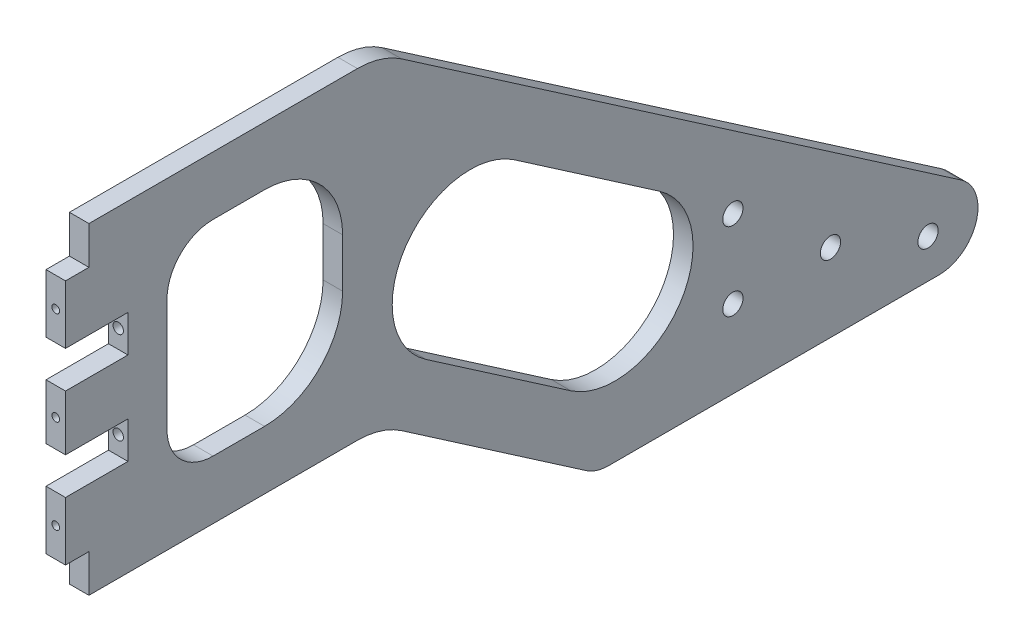
SolidWorks part; units mm, degrees
material "6061 Alloy"
ref_plane "Front Plane" through (0, 0, 0) normal (0, 0, 1) x (1, 0, 0)
ref_plane "Top Plane" through (0, 0, 0) normal (0, 1, 0) x (1, 0, 0)
ref_plane "Right Plane" through (0, 0, 0) normal (1, 0, 0) x (0, 0, -1)
sketch "Sketch1" plane through (0, 0, 0) normal (1, 0, 0) x (0, 0, -1)
  line L0 (124.0703, 0) -> (-28.3297, 0)
  line L1 (55, 0) -> (-55, 0) construction
  line L2 (-28.3297, 0) -> (-98.1797, 48.0219)
  line L3 (-98.1797, 48.0219) -> (-98.1797, 152.7969)
  line L4 (-28.3297, 104.775) -> (124.0703, 0)
  line L5 (-28.3297, 0) -> (-28.3297, 104.775)
  line L6 (-28.3297, 104.775) -> (-98.1797, 152.7969)
  line L7 (-98.1797, 152.7969) -> (-180.7297, 152.7969)
  line L8 (-180.7297, 152.7969) -> (-180.7297, 48.0219)
  line L9 (-180.7297, 48.0219) -> (-98.1797, 48.0219)
  line L10 (-139.4547, 152.7969) -> (-139.4547, 48.0219)
  line L11 (-139.4547, 133.7469) -> (-110.8797, 133.7469)
  line L12 (-110.8797, 133.7469) -> (-110.8797, 67.0719)
  line L13 (-110.8797, 67.0719) -> (-139.4547, 67.0719)
  line L14 (-139.4547, 67.0719) -> (-168.0297, 67.0719)
  line L15 (-168.0297, 67.0719) -> (-168.0297, 133.7469)
  line L16 (-168.0297, 133.7469) -> (-139.4547, 133.7469)
  line L17 (-63.2547, 24.0109) -> (-63.2547, 128.7859)
  line L18 (-63.2547, 76.3984) -> (-28.3297, 52.3875)
  line L19 (-63.2547, 76.3984) -> (-98.1797, 100.4094)
  line L20 (-22.2452, 48.2044) -> (-69.3392, 80.5815) construction
  line L21 (-36.6351, 27.2737) -> (-83.7291, 59.6509)
  line L22 (-7.8554, 69.1351) -> (-54.9494, 101.5122)
  line L23 (-180.7297, 152.7969) -> (-193.4297, 152.7969)
  line L24 (-193.4297, 79.4094) -> (-193.4297, 48.0219)
  line L25 (-193.4297, 48.0219) -> (-180.7297, 48.0219)
  line L26 (-180.7297, 121.4094) -> (-193.4297, 121.4094)
  line L27 (-180.7297, 100.4094) -> (-180.7297, 91.4094)
  line L28 (-180.7297, 91.4094) -> (-193.4297, 91.4094)
  line L29 (-180.7297, 109.4094) -> (-193.4297, 109.4094)
  line L30 (-193.4297, 121.4094) -> (-193.4297, 152.7969)
  line L31 (-193.4297, 91.4094) -> (-193.4297, 109.4094)
  line L32 (-193.4297, 79.4094) -> (-180.7297, 79.4094)
  line L33 (-180.7297, 109.4094) -> (-180.7297, 100.4094)
  line L34 (-180.7297, 100.4094) -> (-180.7297, 91.4094)
  line L35 (-193.4297, 79.4094) -> (-201.0497, 79.4094)
  line L36 (-201.0497, 79.4094) -> (-201.0497, 60.3594)
  line L37 (-201.0497, 60.3594) -> (-193.4297, 60.3594)
  line L38 (-193.4297, 121.4094) -> (-201.0497, 121.4094)
  line L39 (-201.0497, 121.4094) -> (-201.0497, 140.4594)
  line L40 (-201.0497, 140.4594) -> (-193.4297, 140.4594)
  line L41 (-193.4297, 109.4094) -> (-201.0497, 109.4094)
  line L42 (-201.0497, 109.4094) -> (-201.0497, 91.4094)
  line L43 (-201.0497, 91.4094) -> (-193.4297, 91.4094)
  arc A0 (-36.6351, 27.2737) -> (-7.8554, 69.1351) centre (-22.2452, 48.2044) ccw
  arc A1 (-54.9494, 101.5122) -> (-83.7291, 59.6509) centre (-69.3392, 80.5815) ccw
  point P25 (-45.7922, 64.393)
  dimension "D11" = 9
  dimension "D1" = 152.4
  dimension "D2" = 104.775
  dimension "D3" = 152.4
  dimension "D4" = 57.15
  dimension "D5" = 50.8
  dimension "D6" = 82.55
  dimension "D7" = 12.7
  dimension "D8" = 12.7
  dimension "D9" = 19.05
  dimension "D10" = 19.05
  dimension "D12" = 9
  dimension "D13" = 12
  dimension "D14" = 12
  dimension "D15" = 12.7
  dimension "D16" = 19.05
  dimension "D17" = 19.05
  dimension "D18" = 7.62
extrude "Boss-Extrude1" add sketch "Sketch1" along normal blind 6.35 contours A0 L5 L0 L4 L22 | A1 L22 L5 L6 L17 | A1 L17 L6 L3 L19 | A1 L19 L3 L2 L17 L21 | A0 L21 L17 L2 L5 | L12 L13 L10 L9 L3 L7 L11 | L15 L16 L10 L7 L8 L9 L14 | L30 L26 L8 L23 | L40 L39 L38 L30 | L31 L28 L8 L29 | L42 L43 L31 L41 | L36 L37 L24 L35 | L32 L24 L25 L8
fillet "Fillet1" radius 25.4 4 edges at (3.175, 152.7969, 98.1797) (3.175, 48.0219, 98.1797) (3.175, 133.7469, 110.8797) (3.175, 67.0719, 110.8797)
fillet "Fillet2" radius 12.7 2 edges at (3.175, 0, -124.0703) (3.175, 0, 28.3297)
sketch "Sketch3" plane through (6.35, 0, 0) normal (1, 0, 0) x (0, 0, -1)
  line L0 (-28.3297, 0) -> (47.8703, 0)
  line L1 (-31.5802, 2.2347) -> (-91.6789, 43.5525) construction
  line L2 (3.4925, 0) -> (-3.4925, 0) construction
  line L3 (47.8703, 0) -> (47.8703, 25.4)
  line L4 (47.8703, 0) -> (79.6203, 0)
  line L5 (79.6203, 0) -> (79.6203, 12.7)
  line L6 (16.1203, 0) -> (16.1203, 50.8)
  line L7 (47.8703, 25.4) -> (16.1203, 25.4)
  point P5 (47.8703, 25.4)
  point P10 (79.6203, 12.7)
  point P11 (16.1203, 50.8)
  point P13 (16.1203, 25.4)
  dimension "D1" = 76.2
  dimension "D2" = 25.4
  dimension "D3" = 50.8
  dimension "D4" = 31.75
  dimension "D5" = 31.75
  dimension "D6" = 12.7
hole_wizard "M6 Clearance Hole1" positions "Sketch3" profile "Sketch4" hole size "M6" standard "ANSI Metric" end condition through all
sketch "Sketch4" plane through (6.35, 25.4, -16.1203) normal (0, 1, 0) x (0, 0, -1)
  line L0 (0, 0) -> (0, 6.35)
  line L1 (0, 6.35) -> (3.3, 6.35)
  line L2 (3.3, 6.35) -> (3.3, 0)
  line L5 (3.3, 0) -> (0, 0)
  line L11 (0, -6.35) -> (0, 107.95) construction
  dimension "Thru Hole Dia." = 6.6
  dimension "Thru Hole Depth" = 6.35
sketch "Sketch5" plane through (0, 0, 180.7297) normal (0, 0, 1) x (1, 0, 0)
  line L0 (0, 100.4094) -> (6.35, 100.4094)
  line L1 (0, 152.7969) -> (0, 48.0219) construction
  line L2 (6.35, 152.7969) -> (6.35, 48.0219) construction
  line L3 (6.35, 100.4094) -> (6.35, 130.4094)
  line L4 (6.35, 115.4094) -> (0, 115.4094)
  line L5 (6.35, 115.4094) -> (6.35, 121.4094)
  line L6 (6.35, 121.4094) -> (0, 121.4094)
  line L7 (0, 121.4094) -> (0, 115.4094)
  line L8 (0, 109.4094) -> (6.35, 109.4094)
  line L9 (6.35, 109.4094) -> (6.35, 115.4094)
  line L10 (3.175, 121.4094) -> (3.175, 115.4094)
  line L11 (3.175, 115.4094) -> (3.175, 109.4094)
  line L12 (0, 115.4094) -> (0, 109.4094)
  line L13 (6.35, 115.4094) -> (6.35, 109.4094)
  line L14 (6.35, 100.4094) -> (6.35, 70.4094)
  line L15 (6.35, 79.4094) -> (0, 79.4094)
  line L16 (0, 79.4094) -> (0, 91.4094)
  line L17 (0, 91.4094) -> (6.35, 91.4094)
  line L18 (6.35, 91.4094) -> (6.35, 79.4094)
  line L19 (6.35, 85.4094) -> (0, 85.4094)
  line L20 (0, 85.4094) -> (0, 79.4094)
  line L21 (3.175, 79.4094) -> (3.175, 85.4094)
  line L22 (3.175, 85.4094) -> (3.175, 91.4094)
  line L23 (0, 79.4094) -> (0, 66.7094)
  line L24 (0, 66.7094) -> (6.35, 66.7094)
  line L25 (6.35, 66.7094) -> (6.35, 79.4094)
  line L26 (6.35, 121.4094) -> (6.35, 134.1094)
  line L27 (6.35, 134.1094) -> (0, 134.1094)
  line L28 (0, 134.1094) -> (0, 121.4094)
  point P24 (6.35, 85.4094)
  dimension "D1" = 30
  dimension "D2" = 12
  dimension "D3" = 30
  dimension "D4" = 12
  dimension "D5" = 12.7
  dimension "D6" = 12.7
sketch "Sketch6" plane through (0, 0, 180.7297) normal (0, 0, 1) x (1, 0, 0)
  line L0 (0.2811, 100.4094) -> (6.35, 100.4094)
  line L3 (6.35, 100.4094) -> (6.35, 130.4094)
  line L4 (6.35, 115.4094) -> (0, 115.4094)
  line L5 (6.35, 115.4094) -> (6.35, 121.4094)
  line L6 (6.35, 121.4094) -> (0, 121.4094)
  line L7 (0, 121.4094) -> (0, 115.4094)
  line L8 (0, 109.4094) -> (6.35, 109.4094)
  line L9 (6.35, 109.4094) -> (6.35, 115.4094)
  line L10 (3.175, 121.4094) -> (3.175, 115.4094)
  line L11 (3.175, 115.4094) -> (3.175, 109.4094)
  line L12 (0, 115.4094) -> (0, 109.4094)
  line L13 (6.35, 115.4094) -> (6.35, 109.4094)
  line L14 (6.35, 100.4094) -> (6.35, 70.4094)
  line L15 (6.35, 79.4094) -> (0, 79.4094)
  line L16 (0, 79.4094) -> (0, 91.4094)
  line L17 (0, 91.4094) -> (6.35, 91.4094)
  line L18 (6.35, 91.4094) -> (6.35, 79.4094)
  line L19 (6.35, 85.4094) -> (0, 85.4094)
  line L20 (0, 85.4094) -> (0, 79.4094)
  line L21 (3.175, 79.4094) -> (3.175, 85.4094)
  line L22 (3.175, 85.4094) -> (3.175, 91.4094)
  line L23 (0, 79.4094) -> (0, 66.7094)
  line L24 (0, 66.7094) -> (6.35, 66.7094)
  line L25 (6.35, 66.7094) -> (6.35, 79.4094)
  line L26 (6.35, 121.4094) -> (6.35, 134.1094)
  line L27 (6.35, 134.1094) -> (0, 134.1094)
  line L28 (0, 134.1094) -> (0, 121.4094)
  line L29 (6.35, 100.4094) -> (6.35, 130.4094) construction
  line L30 (0, 152.7969) -> (0, 48.0219) construction
  line L31 (0, 100.4094) -> (6.35, 100.4094) construction
  line L32 (6.35, 121.4094) -> (6.35, 134.1094) construction
  point P14 (3.175, 115.4094)
  point P24 (6.35, 85.4094)
  point P26 (3.175, 85.4094)
  dimension "D1" = 30
  dimension "D2" = 12
  dimension "D3" = 30
  dimension "D4" = 12
  dimension "D5" = 12.7
  dimension "D6" = 12.7
hole_wizard "M3 Clearance Hole1" positions "Sketch6" profile "Sketch7" hole size "M3" standard "ANSI Metric"
sketch "Sketch7" plane through (3.175, 85.4094, 180.7297) normal (1, 0, 0) x (0, -1, 0)
  line L0 (0, 0) -> (0, 12.7)
  line L1 (0, 12.7) -> (1.7, 12.7)
  line L2 (1.7, 12.7) -> (1.7, 0)
  line L5 (1.7, 0) -> (0, 0)
  line L11 (0, -6.35) -> (0, 107.95) construction
  dimension "Thru Hole Dia." = 3.4
  dimension "Thru Hole Depth" = 12.7
fillet "Fillet4" radius 15 2 edges at (3.175, 67.0719, 168.0297) (3.175, 133.7469, 168.0297)
sketch "Sketch8" plane through (0, 0, 201.0497) normal (0, 0, 1) x (1, 0, 0)
  line L0 (3.175, 140.4594) -> (3.175, 121.4094)
  line L1 (6.35, 140.4594) -> (0, 140.4594) construction
  line L2 (3.175, 60.3594) -> (3.175, 79.4094)
  line L3 (6.35, 60.3594) -> (0, 60.3594) construction
  line L4 (6.35, 79.4094) -> (0, 79.4094) construction
  line L5 (3.175, 109.4094) -> (3.175, 91.4094)
  line L6 (6.35, 109.4094) -> (0, 109.4094) construction
  line L7 (6.35, 91.4094) -> (0, 91.4094) construction
  point P19 (3.175, 130.9344)
  point P21 (3.175, 100.4094)
  point P23 (3.175, 69.8844)
hole_wizard "M3x0.5 Tapped Hole1" positions "Sketch8" profile "Sketch10" tap size "M3x0.5" standard "ANSI Metric"
sketch "Sketch10" plane through (3.175, 69.8844, 201.0497) normal (1, 0, 0) x (0, -1, 0)
  line L0 (0, 0) -> (0, 26.1511)
  line L1 (0, 26.1511) -> (1.25, 25.4)
  line L2 (1.25, 25.4) -> (1.25, 0)
  line L5 (1.25, 0) -> (0, 0)
  line L10 (0, 26.1511) -> (-1.25, 25.4) construction
  line L11 (0, -6.35) -> (0, 107.95) construction
  dimension "Tap Drill Dia." = 2.5
  dimension "Tap Drill Depth" = 25.4
  dimension "Drill Angle" = 118
cosmetic thread "Hole Thread1" parameters "D1"=19.05, "D2"=3
cosmetic thread "Hole Thread2" parameters "D1"=19.05, "D2"=3
cosmetic thread "Hole Thread3" parameters "D1"=19.05, "D2"=3
